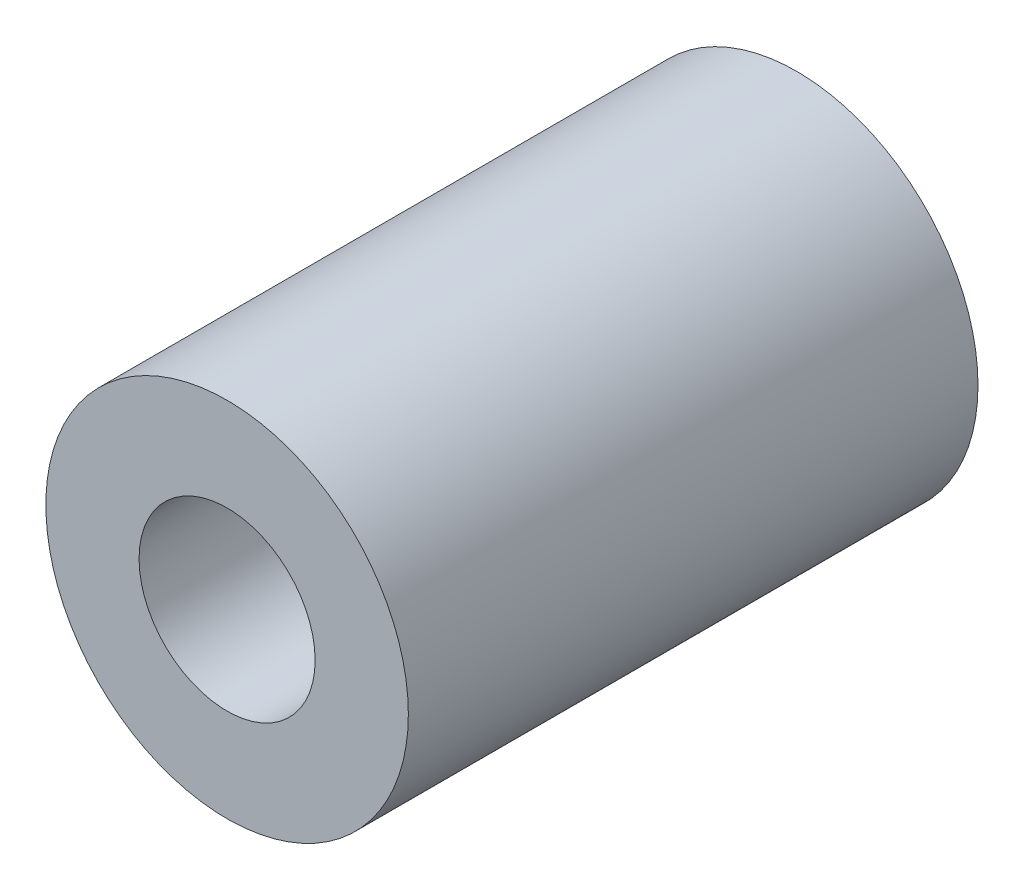
SolidWorks part; units mm, degrees
ref_plane "Front Plane" through (0, 0, 0) normal (0, 0, 1) x (1, 0, 0)
ref_plane "Top Plane" through (0, 0, 0) normal (0, 1, 0) x (1, 0, 0)
ref_plane "Right Plane" through (0, 0, 0) normal (1, 0, 0) x (0, 0, -1)
sketch "Sketch1" plane through (0, 0, 0) normal (0, 0, 1) x (1, 0, 0)
  circle A0 centre (0, 0) radius 1.7
  circle A1 centre (0, 0) radius 3.5
  dimension "D1" = 3.4
  dimension "D2" = 7
extrude "Boss-Extrude1" add sketch "Sketch1" along normal blind 11
